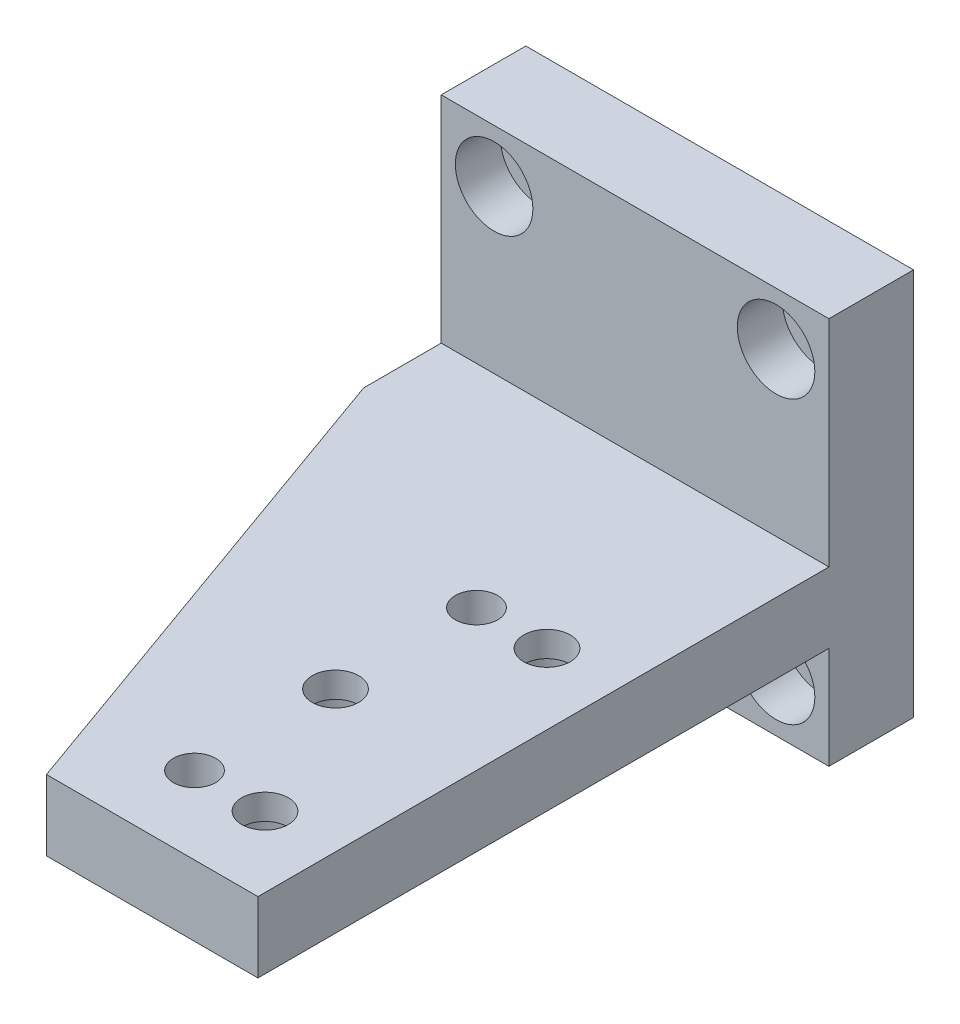
SolidWorks part; units mm, degrees
ref_plane "Front Plane" through (0, 0, 0) normal (0, 0, 1) x (1, 0, 0)
ref_plane "Top Plane" through (0, 0, 0) normal (0, 1, 0) x (1, 0, 0)
ref_plane "Right Plane" through (0, 0, 0) normal (1, 0, 0) x (0, 0, -1)
sketch "Sketch1" plane through (0, 0, 0) normal (0, 0, 1) x (1, 0, 0)
  line L1 (-27.5, 27.5) -> (27.5, 27.5)
  line L2 (-27.5, 27.5) -> (-27.5, -27.5)
  line L3 (-27.5, -27.5) -> (27.5, -27.5)
  line L4 (27.5, 27.5) -> (27.5, -27.5)
  line L5 (-27.5, 27.5) -> (27.5, -27.5) construction
  line L6 (-27.5, -27.5) -> (27.5, 27.5) construction
  point P0 (0, 0)
  dimension "D1" = 55
  dimension "D2" = 55
extrude "Boss-Extrude1" add sketch "Sketch1" along normal mid plane 12 contours L2 L3 L4 L1
hole_wizard "CBORE for M6 Hex Socket Head Cap Screw1" positions "Sketch2" profile "Sketch3" counterbore size "M6" standard "ISO" end condition through all
sketch "Sketch2" plane through (0, 0, 6) normal (0, 0, 1) x (1, 0, 0)
  line L0 (-27.5, -27.5) -> (27.5, -27.5) construction
  point P0 (-20, 20)
  point P2 (20, 20)
  point P4 (20, -20)
  point P6 (-20, -20)
  dimension "D1" = 40
  dimension "D2" = 20
  dimension "D3" = 40
  dimension "D4" = 7.5
sketch "Sketch3" plane through (-20, 20, 6) normal (1, 0, 0) x (0, -1, 0)
  line L0 (0, 0) -> (0, 12)
  line L1 (0, 12) -> (3.3, 12)
  line L3 (3.3, 12) -> (3.3, 6.4)
  line L4 (3.3, 6.4) -> (5.5, 6.4)
  line L5 (5.5, 6.4) -> (5.5, 0)
  line L7 (5.5, 0) -> (0, 0)
  line L11 (0, -6.35) -> (0, 107.95) construction
  dimension "Thru Hole Dia." = 6.6
  dimension "Thru Hole Depth" = 12
  dimension "C'Bore Dia." = 11
  dimension "C'Bore Depth" = 6.4
sketch "Sketch4" plane through (0, 0, 6) normal (0, 0, 1) x (1, 0, 0)
  line L0 (-27.5, 27.5) -> (-27.5, -27.5) construction
  line L1 (-27.5, -3) -> (27.5, -3)
  line L2 (-27.5, -3) -> (-27.5, -13)
  line L3 (-27.5, -13) -> (27.5, -13)
  line L4 (27.5, -3) -> (27.5, -13)
  line L5 (27.5, 27.5) -> (27.5, -27.5) construction
  line L6 (-27.5, -27.5) -> (27.5, -27.5) construction
  dimension "D1" = 3
  dimension "D2" = 10
  dimension "D3" = 24.5
extrude "Boss-Extrude2" add sketch "Sketch4" along normal blind 81
hole_wizard "CBORE for M6 Hex Socket Head Cap Screw2" positions "Sketch5" profile "Sketch6" counterbore size "M6" standard "ISO" end condition through all
sketch "Sketch5" plane through (0, -13, 0) normal (0, -1, 0) x (-1, 0, 0)
  line L0 (-27.5, -87) -> (-27.5, -6) construction
  line L1 (27.5, -6) -> (-27.5, -6) construction
  point P0 (-17.5, -76)
  point P2 (-7.5, -56)
  point P4 (-17.5, -36)
  dimension "D1" = 10
  dimension "D2" = 10
  dimension "D3" = 30
  dimension "D4" = 20
  dimension "D5" = 20
sketch "Sketch6" plane through (17.5, -13, 76) normal (1, 0, 0) x (0, 0, -1)
  line L0 (0, 0) -> (0, 40.5)
  line L1 (0, 40.5) -> (3.3, 40.5)
  line L3 (3.3, 40.5) -> (3.3, 6.4)
  line L4 (3.3, 6.4) -> (5.5, 6.4)
  line L5 (5.5, 6.4) -> (5.5, 0)
  line L7 (5.5, 0) -> (0, 0)
  line L11 (0, -6.35) -> (0, 107.95) construction
  dimension "Thru Hole Dia." = 6.6
  dimension "Thru Hole Depth" = 40.5
  dimension "C'Bore Dia." = 11
  dimension "C'Bore Depth" = 6.4
chamfer "Chamfer1" distance 70 distance2 25 1 edges at (-27.5, -8, 87)
hole_wizard "Ø6.0mm Dowel Hole1" positions "Sketch9" profile "Sketch10" hole size "Ø6.0" standard "JIS" end condition through all
sketch "Sketch9" plane through (0, -13, 0) normal (0, -1, 0) x (-1, 0, 0)
  circle A0 centre (-17.5, -36) radius 3.3 construction
  circle A1 centre (-7.5, -56) radius 3.3 construction
  circle A2 centre (-7.5, -56) radius 5.5 construction
  point P0 (-7.5, -36)
  point P2 (-7.5, -76)
  point P5 (0, 0)
  dimension "D1" = 10
  dimension "D3" = 20
  dimension "D2" = 20
sketch "Sketch10" plane through (7.5, -13, 36) normal (1, 0, 0) x (0, 0, -1)
  line L0 (0, 0) -> (0, 40.5)
  line L1 (0, 40.5) -> (3, 40.5)
  line L2 (3, 40.5) -> (3, 0)
  line L5 (3, 0) -> (0, 0)
  line L11 (0, -6.35) -> (0, 107.95) construction
  dimension "Thru Hole Dia." = 6
  dimension "Thru Hole Depth" = 40.5
